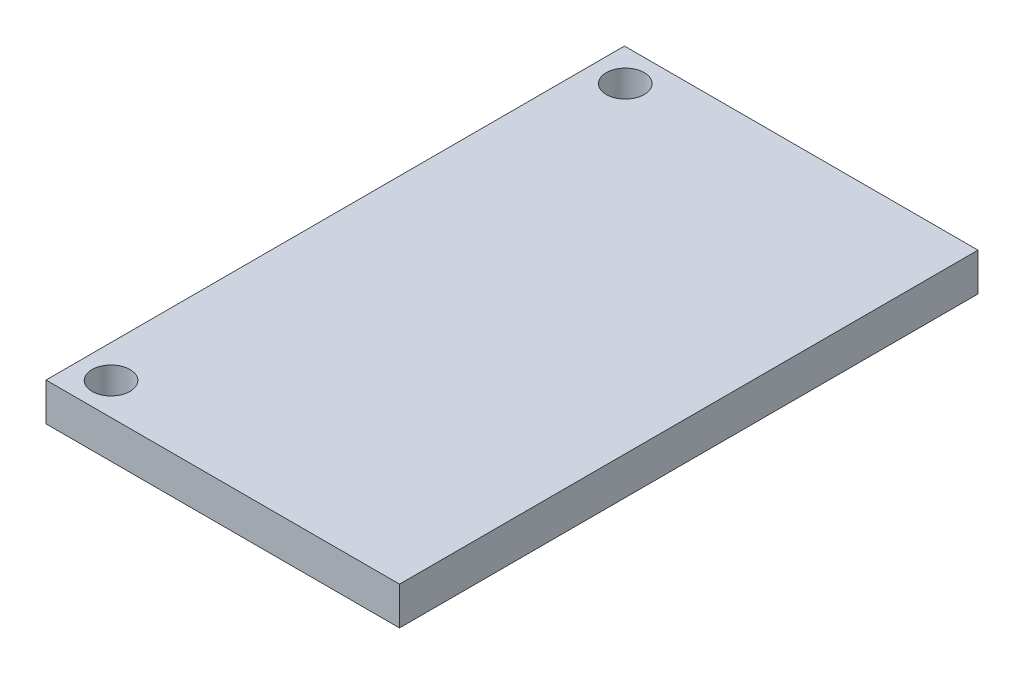
SolidWorks part; units mm, degrees
ref_plane "Alzado" through (0, 0, 0) normal (0, 0, 1) x (1, 0, 0)
ref_plane "Planta" through (0, 0, 0) normal (0, 1, 0) x (1, 0, 0)
ref_plane "Vista lateral" through (0, 0, 0) normal (1, 0, 0) x (0, 0, -1)
sketch "Croquis2" plane through (0, 0, 0) normal (0, 1, 0) x (1, 0, 0)
  line L1 (0, 0) -> (27.94, 0)
  line L2 (0, 0) -> (0, -45.72)
  line L3 (0, -45.72) -> (27.94, -45.72)
  line L4 (27.94, 0) -> (27.94, -45.72)
  dimension "D1" = 45.72
  dimension "D2" = 27.94
extrude "Saliente-Extruir2" add sketch "Croquis2" along normal blind 3
sketch "Croquis3" plane through (0, 3, 0) normal (0, 1, 0) x (1, 0, 0)
  line L0 (0, -45.72) -> (27.94, -45.72) construction
  line L1 (27.94, 0) -> (0, 0) construction
  line L2 (0, 0) -> (0, -45.72) construction
  circle A0 centre (2.6, -2.54) radius 1.5
  circle A1 centre (2.6, -43.18) radius 1.5
  dimension "D1" = 2.54
  dimension "D2" = 2.54
  dimension "D3" = 3
  dimension "D4" = 3
  dimension "D5" = 2.6
  dimension "D6" = 2.6
extrude "Cortar-Extruir1" cut sketch "Croquis3" against normal through all
